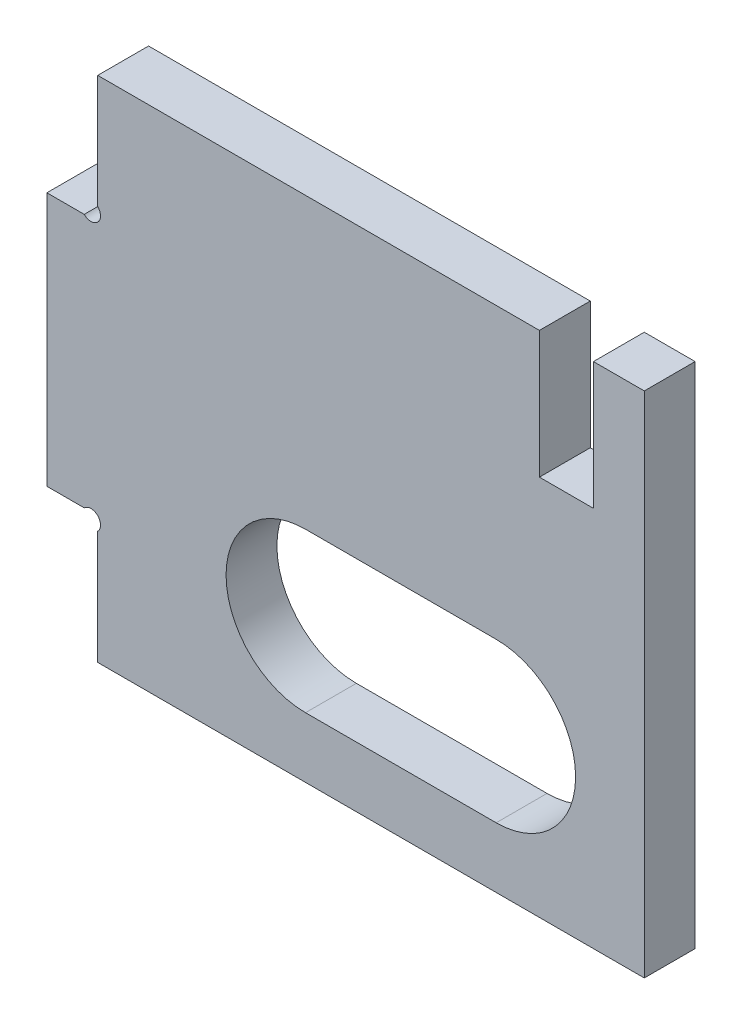
SolidWorks part; units mm, degrees
ref_plane "Plan de face" through (0, 0, 0) normal (0, 0, 1) x (1, 0, 0)
ref_plane "Plan de dessus" through (0, 0, 0) normal (0, 1, 0) x (1, 0, 0)
ref_plane "Plan de droite" through (0, 0, 0) normal (1, 0, 0) x (0, 0, -1)
sketch "Esquisse1" plane through (0, 0, 0) normal (0, 0, 1) x (1, 0, 0)
  line L0 (-48.2063, 70.5712) -> (-48.2063, 52.6925)
  line L1 (-50.3276, 50.5712) -> (-56.2063, 50.5712)
  line L2 (-56.2063, 50.5712) -> (-56.2063, 10.5712)
  line L3 (-56.2063, 10.5712) -> (-50.3276, 10.5712)
  line L4 (-48.2063, 8.4499) -> (-48.2063, -9.4288)
  line L5 (-48.2063, -9.4288) -> (37.7937, -9.4288)
  line L6 (37.7937, -9.4288) -> (37.7937, 70.5712)
  line L7 (37.7937, 70.5712) -> (29.7937, 70.5712)
  line L8 (29.7937, 70.5712) -> (29.7937, 50.5712)
  line L9 (29.7937, 50.5712) -> (21.2937, 50.5712)
  line L10 (21.2937, 50.5712) -> (21.2937, 70.5712)
  line L11 (21.2937, 70.5712) -> (-48.2063, 70.5712)
  line L12 (37.7937, 12.5712) -> (-56.2063, 12.5712) construction
  line L13 (-15.5112, 12.5712) -> (14.4888, 12.5712) construction
  line L14 (-15.5112, 25.0712) -> (14.4888, 25.0712)
  line L15 (-15.5112, 0.0712) -> (14.4888, 0.0712)
  arc A0 (-50.3276, 50.5712) -> (-48.2063, 52.6925) centre (-49.2669, 51.6319) ccw
  arc A1 (-48.2063, 8.4499) -> (-50.3276, 10.5712) centre (-49.2669, 9.5106) ccw
  arc A2 (-15.5112, 25.0712) -> (-15.5112, 0.0712) centre (-15.5112, 12.5712) ccw
  arc A3 (14.4888, 0.0712) -> (14.4888, 25.0712) centre (14.4888, 12.5712) ccw
  point P20 (-0.5112, 12.5712)
  dimension "D6" = 22
  dimension "D1" = 86
  dimension "D2" = 80
  dimension "D3" = 8
  dimension "D4" = 8.5
  dimension "D5" = 40
  dimension "D9" = 20
  dimension "D10" = 20
extrude "Boss.-Extru.1" add sketch "Esquisse1" along normal blind 8
